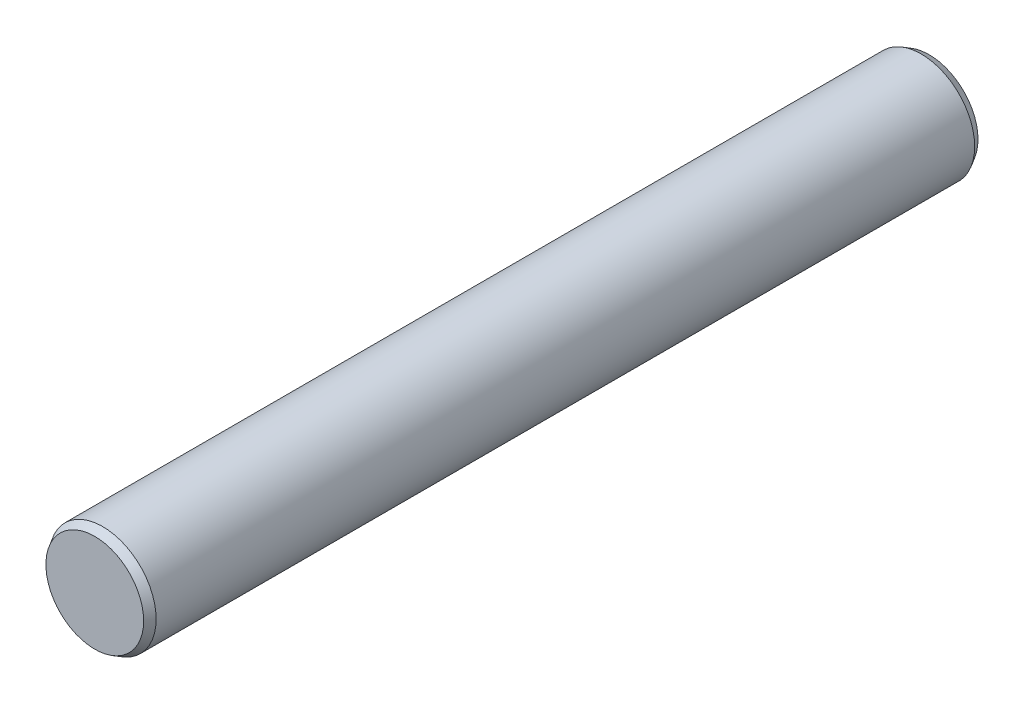
SolidWorks part; units mm, degrees
material "Cast Stainless Steel"
ref_plane "Front" through (0, 0, 0) normal (0, 0, 1) x (1, 0, 0)
ref_plane "Top" through (0, 0, 0) normal (0, 1, 0) x (1, 0, 0)
ref_plane "Right" through (0, 0, 0) normal (1, 0, 0) x (0, 0, -1)
sketch "Sketch2" plane through (0, 0, 0) normal (0, 0, 1) x (1, 0, 0)
  circle A0 centre (0, 0) radius 1.7145
  dimension "D1" = 3.429
extrude "Extrude1" add sketch "Sketch2" along normal mid plane 26.7716
chamfer "Chamfer1" distance 0.254 angle 30 1 edges at (1.7145, 0, 13.3858)
chamfer "Chamfer2" distance 0.254 angle 30 1 edges at (1.7145, 0, -13.3858)
